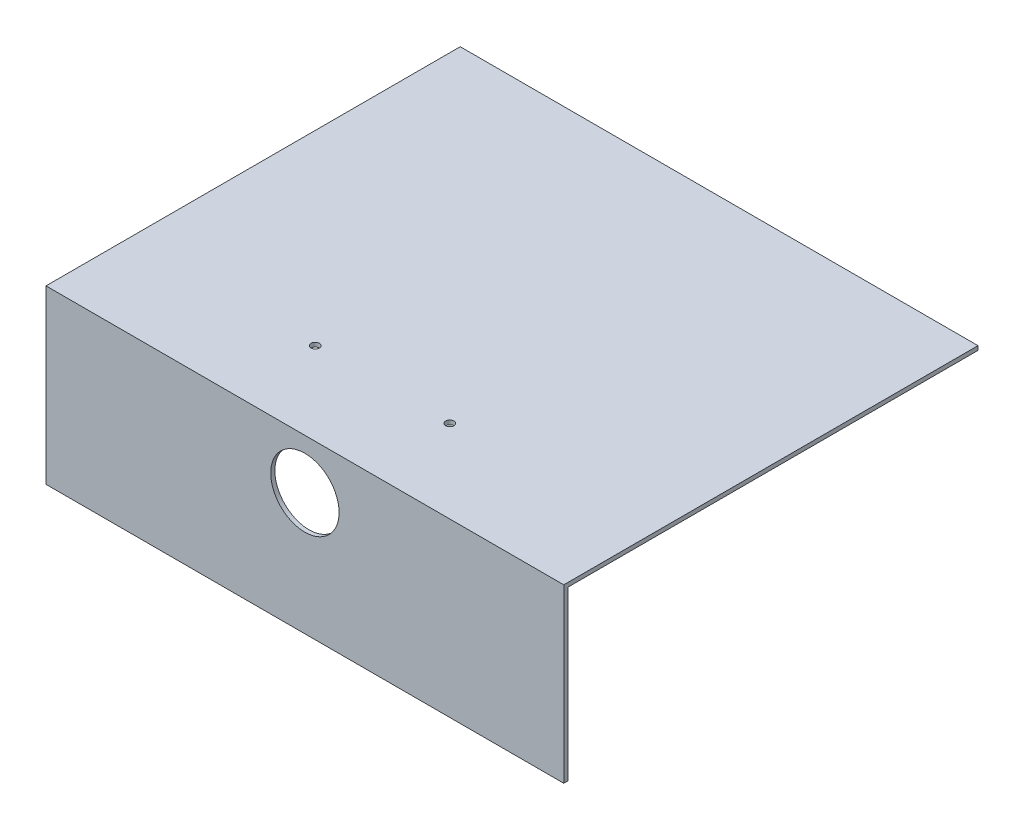
SolidWorks part; units mm, degrees
ref_plane "Front Plane" through (0, 0, 0) normal (0, 0, 1) x (1, 0, 0)
ref_plane "Top Plane" through (0, 0, 0) normal (0, 1, 0) x (1, 0, 0)
ref_plane "Right Plane" through (0, 0, 0) normal (1, 0, 0) x (0, 0, -1)
sketch "Sketch1" plane through (0, 0, 0) normal (0, 1, 0) x (1, 0, 0)
  line L1 (0, 0) -> (250, 0)
  line L2 (0, 0) -> (0, 200)
  line L3 (0, 200) -> (250, 200)
  line L4 (250, 0) -> (250, 200)
  dimension "D1" = 250
  dimension "D2" = 200
extrude "Boss-Extrude1" add sketch "Sketch1" along normal blind 2
sketch "Sketch2" plane through (0, 0, 0) normal (0, -1, 0) x (1, 0, 0)
  line L0 (250, 0) -> (250, -200) construction
  line L1 (0, 0) -> (250, 0)
  line L2 (0, 0) -> (0, -2)
  line L3 (0, -2) -> (250, -2)
  line L4 (250, 0) -> (250, -2)
  dimension "D1" = 2
extrude "Boss-Extrude2" add sketch "Sketch2" along normal blind 81
sketch "Sketch3" plane through (0, 2, 0) normal (0, 1, 0) x (1, 0, 0)
  line L1 (0, 200) -> (0, 0) construction
  line L2 (30.5599, 175) -> (30.5599, 25) construction
  line L3 (30.5599, 175) -> (30.5599, 200) construction
  line L4 (250, 200) -> (0, 200) construction
  line L5 (30.5599, 25) -> (30.5599, 0) construction
  line L6 (0, 0) -> (250, 0) construction
  circle A0 centre (155, 40) radius 2
  circle A1 centre (90, 40) radius 2
  dimension "D3" = 4
  dimension "D4" = 4
  dimension "D1" = 150
  dimension "D2" = 65
  dimension "D5" = 90
  dimension "D6" = 15
extrude "Cut-Extrude1" cut sketch "Sketch3" against normal through all
sketch "Sketch4" plane through (0, 0, 0) normal (0, 0, 1) x (1, 0, 0)
  circle A0 centre (125, -22) radius 16.5
  dimension "D1" = 33
extrude "Cut-Extrude2" cut sketch "Sketch4" against normal up to next
